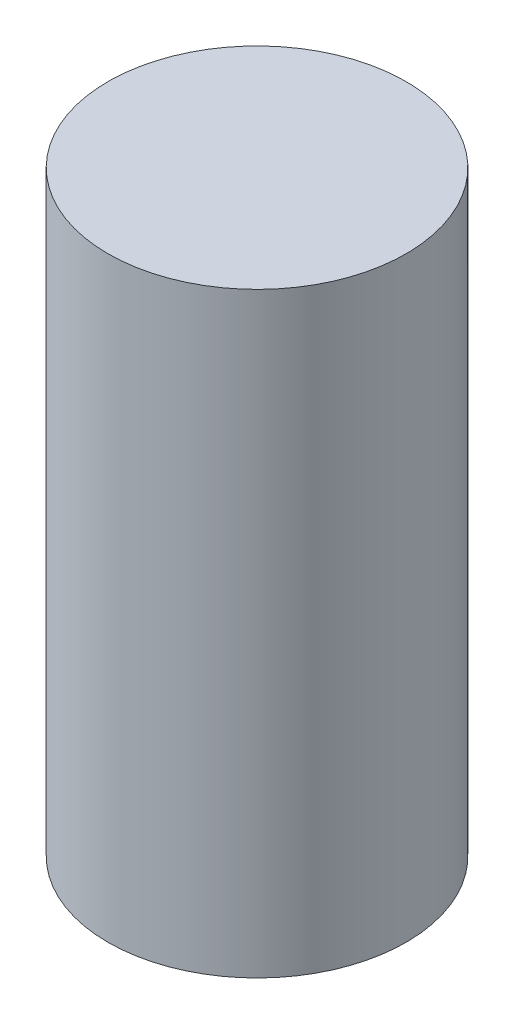
SolidWorks part; units mm, degrees
ref_plane "Front Plane" through (0, 0, 0) normal (0, 0, 1) x (1, 0, 0)
ref_plane "Top Plane" through (0, 0, 0) normal (0, 1, 0) x (1, 0, 0)
ref_plane "Right Plane" through (0, 0, 0) normal (1, 0, 0) x (0, 0, -1)
sketch "Sketch1" plane through (0, 0, 0) normal (0, 1, 0) x (1, 0, 0)
  circle A0 centre (0, 0) radius 6.35
  dimension "D1" = 12.7
extrude "Boss-Extrude1" add sketch "Sketch1" along normal mid plane 25.4
